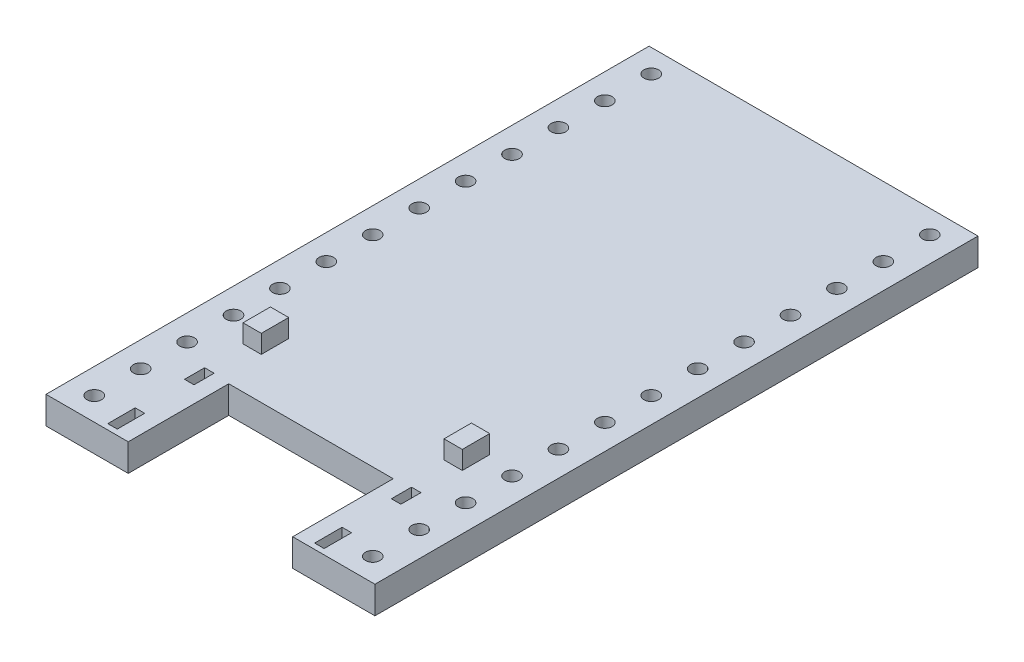
SolidWorks part; units mm, degrees
ref_plane "Front Plane" through (0, 0, 0) normal (0, 0, 1) x (1, 0, 0)
ref_plane "Top Plane" through (0, 0, 0) normal (0, 1, 0) x (1, 0, 0)
ref_plane "Right Plane" through (0, 0, 0) normal (1, 0, 0) x (0, 0, -1)
sketch "Sketch1" plane through (0, 0, 0) normal (0, 1, 0) x (1, 0, 0)
  line L0 (0, 0) -> (0, 33) construction
  line L1 (-7.62, 16.5) -> (7.62, 16.5) construction
  line L2 (-9, 33) -> (9, 33)
  line L3 (-9, 33) -> (-9, 0)
  line L4 (-9, 0) -> (-4.5, 0)
  line L5 (9, 33) -> (9, 0)
  line L6 (-4.5, 0) -> (-4.5, 5.5)
  line L7 (-4.5, 5.5) -> (4.5, 5.5)
  line L8 (4.5, 5.5) -> (4.5, 0)
  line L9 (4.5, 0) -> (9, 0)
  line L11 (5.4, 5.6) -> (5.92, 5.6)
  line L12 (5.4, 5.6) -> (5.4, 4.5)
  line L13 (5.4, 4.5) -> (5.92, 4.5)
  line L14 (5.92, 5.6) -> (5.92, 4.5)
  line L15 (5.4, 1.8) -> (5.92, 1.8)
  line L16 (5.4, 1.8) -> (5.4, 0.3)
  line L17 (5.4, 0.3) -> (5.92, 0.3)
  line L18 (5.92, 1.8) -> (5.92, 0.3)
  line L24 (-5.92, 1.8) -> (-5.92, 0.3)
  line L25 (-5.4, 0.3) -> (-5.92, 0.3)
  line L26 (-5.4, 1.8) -> (-5.4, 0.3)
  line L27 (-5.4, 1.8) -> (-5.92, 1.8)
  line L28 (-5.92, 5.6) -> (-5.92, 4.5)
  line L29 (-5.4, 4.5) -> (-5.92, 4.5)
  line L30 (-5.4, 5.6) -> (-5.4, 4.5)
  line L31 (-5.4, 5.6) -> (-5.92, 5.6)
  circle A0 centre (7.62, 1.26) radius 0.4
  circle A1 centre (7.62, 3.8) radius 0.4
  circle A2 centre (7.62, 6.34) radius 0.4
  circle A3 centre (7.62, 8.88) radius 0.4
  circle A4 centre (7.62, 11.42) radius 0.4
  circle A5 centre (7.62, 13.96) radius 0.4
  circle A6 centre (7.62, 16.5) radius 0.4
  circle A7 centre (7.62, 19.04) radius 0.4
  circle A8 centre (7.62, 21.58) radius 0.4
  circle A9 centre (7.62, 24.12) radius 0.4
  circle A10 centre (7.62, 26.66) radius 0.4
  circle A11 centre (7.62, 29.2) radius 0.4
  circle A12 centre (7.62, 31.74) radius 0.4
  circle A13 centre (-7.62, 31.74) radius 0.4
  circle A14 centre (-7.62, 29.2) radius 0.4
  circle A15 centre (-7.62, 26.66) radius 0.4
  circle A16 centre (-7.62, 24.12) radius 0.4
  circle A17 centre (-7.62, 21.58) radius 0.4
  circle A18 centre (-7.62, 19.04) radius 0.4
  circle A19 centre (-7.62, 16.5) radius 0.4
  circle A20 centre (-7.62, 13.96) radius 0.4
  circle A21 centre (-7.62, 11.42) radius 0.4
  circle A22 centre (-7.62, 8.88) radius 0.4
  circle A23 centre (-7.62, 6.34) radius 0.4
  circle A24 centre (-7.62, 3.8) radius 0.4
  circle A25 centre (-7.62, 1.26) radius 0.4
  point P7 (0, 33)
  point P10 (0, 16.5)
  point P11 (0, 16.5)
  point P14 (0, 5.5)
  dimension "D4" = 0.8
  dimension "D1" = 33
  dimension "D2" = 18
  dimension "D3" = 15.24
  dimension "D6" = 2.54
  dimension "D7" = 5.5
  dimension "D8" = 9
  dimension "D9" = 0.52
  dimension "D10" = 3.08
  dimension "D11" = 0.3
  dimension "D12" = 1.5
  dimension "D13" = 1.1
  dimension "D14" = 2.7
  dimension "D5" = 13
extrude "Boss-Extrude1" add sketch "Sketch1" against normal blind 1.5
sketch "Sketch2" plane through (0, 0, 0) normal (0, 1, 0) x (1, 0, 0)
  line L0 (0, 5.5) -> (0, 33) construction
  line L1 (-6, 9.28) -> (-5, 9.28)
  line L2 (-6, 9.28) -> (-6, 7.78)
  line L3 (-6, 7.78) -> (-5, 7.78)
  line L4 (-5, 9.28) -> (-5, 7.78)
  line L5 (-4.5, 5.5) -> (4.5, 5.5) construction
  line L6 (9, 33) -> (-9, 33) construction
  line L7 (5, 9.28) -> (5, 7.78)
  line L8 (6, 7.78) -> (5, 7.78)
  line L9 (6, 9.28) -> (6, 7.78)
  line L10 (6, 9.28) -> (5, 9.28)
  line L11 (-6, 9.28) -> (-5, 7.78) construction
  line L12 (6, 9.28) -> (5, 7.78) construction
  circle A0 centre (-7.62, 8.88) radius 0.4 construction
  point P16 (-5.5, 8.53)
  point P17 (5.5, 8.53)
  dimension "D1" = 1.5
  dimension "D2" = 1
  dimension "D3" = 10
extrude "Boss-Extrude2" add sketch "Sketch2" along normal blind 1
